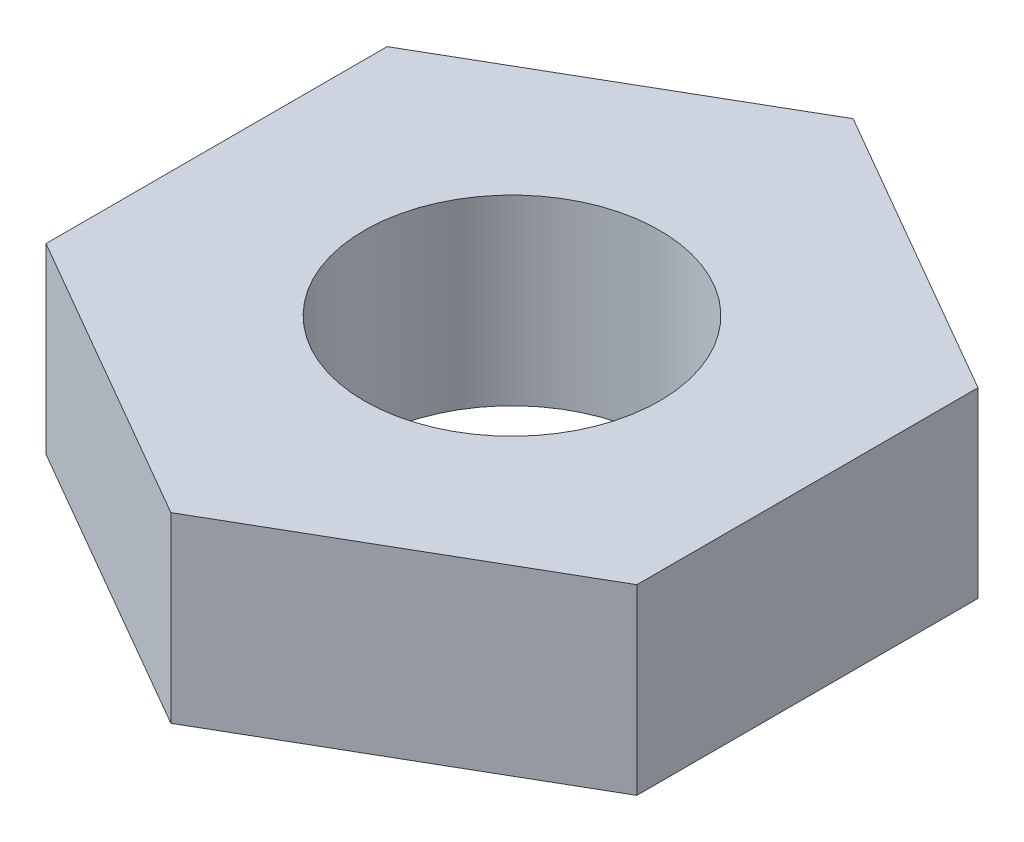
SolidWorks part; units mm, degrees
ref_plane "Front Plane" through (0, 0, 0) normal (0, 0, 1) x (1, 0, 0)
ref_plane "Top Plane" through (0, 0, 0) normal (0, 1, 0) x (1, 0, 0)
ref_plane "Right Plane" through (0, 0, 0) normal (1, 0, 0) x (0, 0, -1)
sketch "Sketch1" plane through (0, 0, 0) normal (0, 1, 0) x (1, 0, 0)
  line L0 (3.4544, 1.9944) -> (3.4544, -1.9944)
  line L1 (-3.4544, 1.9944) -> (-3.4544, -1.9944)
  line L2 (3.4544, 1.9944) -> (0, 3.9888)
  line L3 (0, 3.9888) -> (-3.4544, 1.9944)
  line L4 (-3.4544, -1.9944) -> (0, -3.9888)
  line L5 (0, -3.9888) -> (3.4544, -1.9944)
  line L6 (-3.4544, 0) -> (0, 0) construction
  line L7 (0, 0) -> (3.4544, 0) construction
  circle A0 centre (0, 0) radius 1.7272
  dimension "D2" = 3.4544
  dimension "D1" = 6.9088
  dimension "D3" = 240
extrude "Boss-Extrude1" add sketch "Sketch1" along normal blind 2.1336
